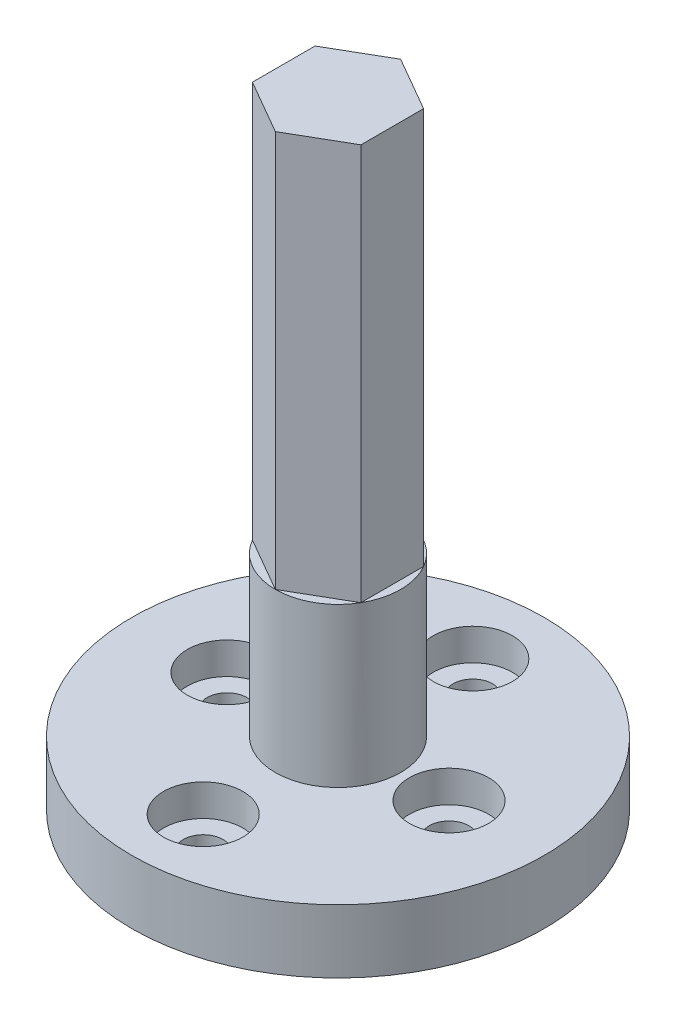
SolidWorks part; units mm, degrees
ref_plane "Alzado" through (0, 0, 0) normal (0, 0, 1) x (1, 0, 0)
ref_plane "Planta" through (0, 0, 0) normal (0, 1, 0) x (1, 0, 0)
ref_plane "Vista lateral" through (0, 0, 0) normal (1, 0, 0) x (0, 0, -1)
sketch "Croquis3" plane through (0, 0, 0) normal (0, 1, 0) x (1, 0, 0)
  circle A0 centre (0, 0) radius 13
  dimension "D1" = 26
extrude "Saliente-Extruir1" add sketch "Croquis3" along normal blind 4
sketch "Croquis4" plane through (0, 4, 0) normal (0, 1, 0) x (1, 0, 0)
  circle A0 centre (0, 0) radius 3.95
  dimension "D1" = 7.9
extrude "Saliente-Extruir2" add sketch "Croquis4" along normal blind 35
sketch "Croquis7" plane through (0, 0, 0) normal (0, -1, 0) x (1, 0, 0)
  circle A0 centre (0, 0) radius 12
  dimension "D1" = 24
sketch "Croquis8" plane through (0, 0, 0) normal (0, -1, 0) x (1, 0, 0)
  line L0 (0, -10.2812) -> (0, 10.4112) construction
  line L1 (-11.52, 0) -> (11.5297, 0) construction
  circle A1 centre (0, 8.5) radius 1.25
  circle A2 centre (0, -8.5) radius 1.25
  circle A3 centre (-7, 0) radius 1.25
  circle A4 centre (7, 0) radius 1.25
  dimension "D1" = 8.5
  dimension "D2" = 2.5
  dimension "D3" = 7
extrude "Cortar-Extruir3" cut sketch "Croquis8" against normal through all both and the other way through all
sketch "Croquis10" plane through (0, 4, 0) normal (0, 1, 0) x (1, 0, 0)
  circle A0 centre (0, -8.5) radius 1.25 construction
  circle A1 centre (0, 8.5) radius 1.25 construction
  circle A2 centre (0, -8.5) radius 1.25 construction
  circle A3 centre (0, 8.5) radius 1.25 construction
  circle A4 centre (0, 8.5) radius 2.5
  circle A5 centre (0, -8.5) radius 2.5
  circle A6 centre (7, 0) radius 1.25 construction
  circle A7 centre (-7, 0) radius 1.25 construction
  circle A8 centre (7, 0) radius 1.25
  circle A9 centre (-7, 0) radius 1.25
  circle A10 centre (-7, 0) radius 2.5
  circle A11 centre (7, 0) radius 2.5
  dimension "D1" = 5
  dimension "D2" = 5
extrude "Cortar-Extruir5" cut sketch "Croquis10" against normal blind 2 and the other way through all
sketch "Croquis9" plane through (0, 0, 0) normal (0, 1, 0) x (1, 0, 0)
  circle A0 centre (0, 0) radius 1.625
  dimension "D1" = 3.25
extrude "Cortar-Extruir4" cut sketch "Croquis9" along normal blind 3
sketch "Croquis12" plane through (0, 39, 0) normal (0, 1, 0) x (1, 0, 0)
  line L1 (0, 3.95) -> (-3.4208, 1.975)
  line L2 (-3.4208, 1.975) -> (-3.4208, -1.975)
  line L3 (-3.4208, -1.975) -> (0, -3.95)
  line L4 (0, -3.95) -> (3.4208, -1.975)
  line L5 (3.4208, -1.975) -> (3.4208, 1.975)
  line L6 (3.4208, 1.975) -> (0, 3.95)
  circle A0 centre (0, 0) radius 3.95 construction
  circle A1 centre (0, 0) radius 3.95 construction
  circle A2 centre (0, 0) radius 3.95 construction
extrude "Cortar-Extruir7" cut sketch "Croquis12" against normal blind 25 flip side to cut
